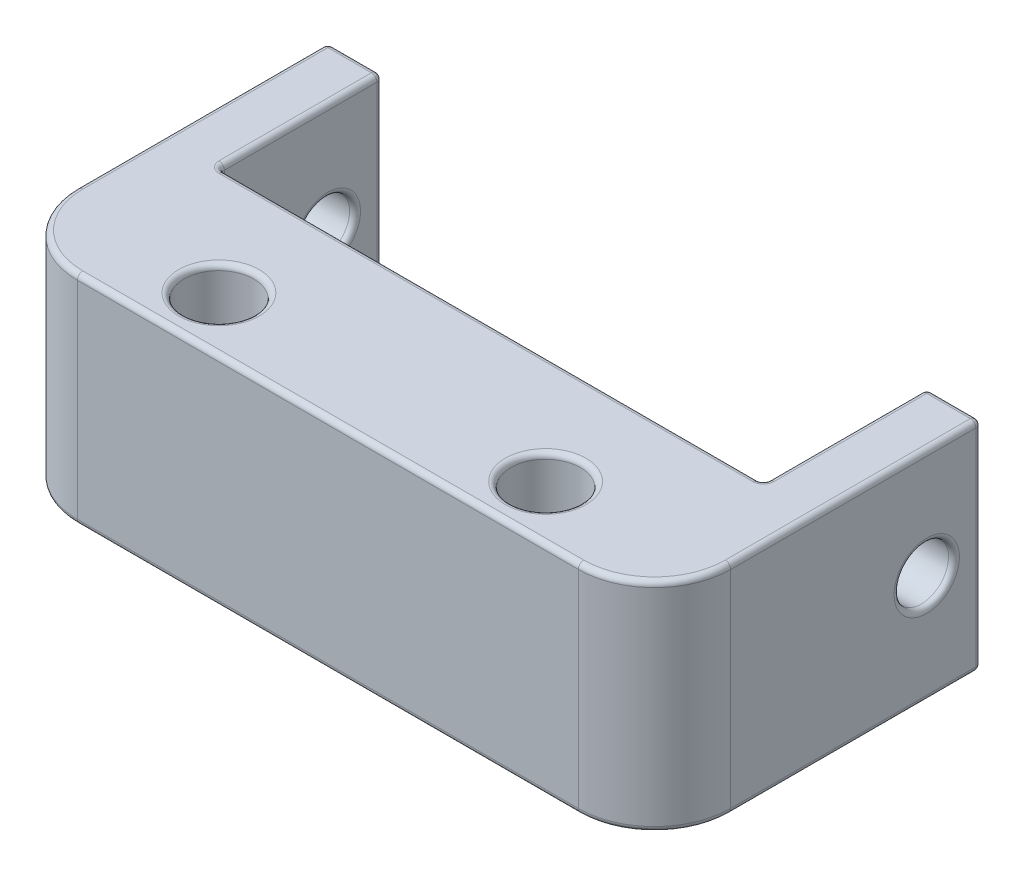
SolidWorks part; units mm, degrees
ref_plane "Front Plane" through (0, 0, 0) normal (0, 0, 1) x (1, 0, 0)
ref_plane "Top Plane" through (0, 0, 0) normal (0, 1, 0) x (1, 0, 0)
ref_plane "Right Plane" through (0, 0, 0) normal (1, 0, 0) x (0, 0, -1)
sketch "Sketch1" plane through (0, 0, 0) normal (0, 1, 0) x (1, 0, 0)
  line L0 (-25, -5) -> (-25, 10)
  line L1 (-30, -10) -> (30, -10)
  line L2 (-30, -10) -> (-30, 10)
  line L3 (-30, 10) -> (30, 10)
  line L4 (30, -10) -> (30, 10)
  line L5 (-30, -10) -> (30, 10) construction
  line L6 (-30, 10) -> (30, -10) construction
  line L8 (25, -5) -> (25, 10)
  line L9 (-25, -5) -> (25, -5)
  line L10 (-25, 5) -> (25, 5) construction
  line L11 (-25, -5) -> (-25, 5) construction
  line L12 (25, -5) -> (25, 5) construction
  line L13 (-30, -11.5) -> (30, -11.5) construction
  line L14 (-30, -10) -> (30, -10)
  line L15 (-30, -10) -> (-30, -13)
  line L16 (-23, -20) -> (23, -20)
  line L17 (30, -10) -> (30, -13)
  line L18 (-30, -20) -> (0, -20) construction
  line L19 (0, -20) -> (0, 10) construction
  circle A0 centre (-15, -15) radius 3.2
  circle A1 centre (15, -15) radius 3.2
  arc A2 (23, -20) -> (30, -13) centre (23, -13) ccw
  arc A3 (-30, -13) -> (-23, -20) centre (-23, -13) ccw
  point P0 (0, 0)
  point P19 (-15, -15)
  dimension "D5" = 6.4
  dimension "D6" = 7
  dimension "D1" = 20
  dimension "D2" = 60
  dimension "D4" = 10
  dimension "D3" = 5
extrude "Boss-Extrude1" add sketch "Sketch1" along normal blind 20 contours L9 L0 L3 L2 L1 L4 L8 | L15 A3 L16 A2 L17 L1 A1 A0
sketch "Sketch2" plane through (-30, 0, 0) normal (-1, 0, 0) x (0, 0, 1)
  line L0 (-10, 10) -> (-5, 10) construction
  line L1 (-10, 20) -> (-10, 0) construction
  circle A0 centre (-5, 10) radius 2.5
  dimension "D2" = 5
  dimension "D1" = 5
extrude "Cut-Extrude1" cut sketch "Sketch2" against normal blind 70
fillet "Fillet1" radius 0.5 34 edges at (25, 10, 5) (-15, 0, 18.2) (15, 0, 18.2) (-27.9497, 0, 17.9497) (0, 0, 20) (27.9497, 0, 17.9497) (25, 0, -2.5) (0, 0, 5) (30, 0, 1.5) (30, 10, -2.5) (-25, 10, 5) (-25, 0, -2.5) (-25, 10, -2.5) (-25, 10, -10) (-27.5, 0, -10) (-30, 10, -10) (-30, 0, 1.5) (-30, 10, -2.5) (30, 10, -10) (25, 10, -10) (27.5, 0, -10) (-15, 20, 18.2) (15, 20, 18.2) (25, 20, -2.5) (27.5, 20, -10) (30, 20, 1.5) (27.9497, 20, 17.9497) (0, 20, 20) (-27.9497, 20, 17.9497) (-30, 20, 1.5) (-27.5, 20, -10) (-25, 20, -2.5) (0, 20, 5) (25, 10, -2.5)
